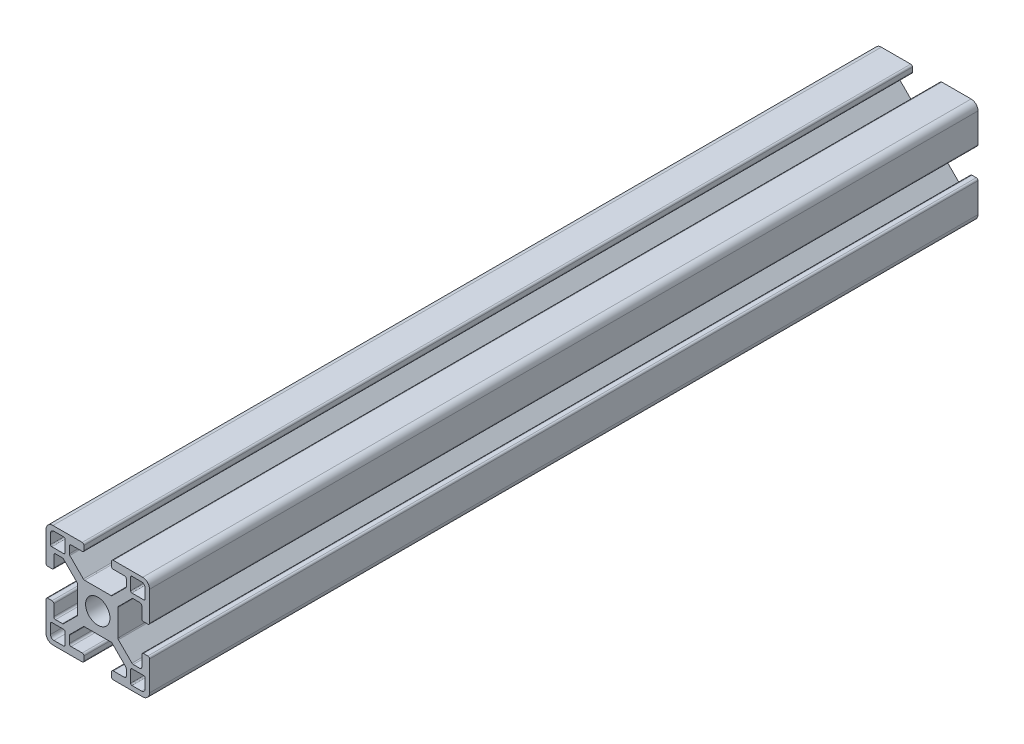
SolidWorks part; units mm, degrees
material "6063-T6"
ref_plane "Front Plane" through (0, 0, 0) normal (0, 0, 1) x (1, 0, 0)
ref_plane "Top Plane" through (0, 0, 0) normal (0, 1, 0) x (1, 0, 0)
ref_plane "Right Plane" through (0, 0, 0) normal (1, 0, 0) x (0, 0, -1)
sketch "Sketch1" plane through (0, 0, 0) normal (0, 0, 1) x (1, 0, 0)
  line L0 (3.9799, -2.4733) -> (3.1981, -1.4942) construction
  line L1 (1.4942, -3.1981) -> (2.4733, -3.9799) construction
  line L2 (-2.4733, -3.9799) -> (-1.4942, -3.1981) construction
  line L3 (-3.1981, -1.4942) -> (-3.9799, -2.4733) construction
  line L4 (-3.9799, 2.4733) -> (-3.1981, 1.4942) construction
  line L5 (-1.4942, 3.1981) -> (-2.4733, 3.9799) construction
  line L6 (2.4733, 3.9799) -> (1.4942, 3.1981) construction
  line L7 (3.1981, 1.4942) -> (3.9799, 2.4733) construction
  line L8 (-12.6999, -13.6999) -> (-9.881, -13.6999)
  line L9 (-13.6999, -9.881) -> (-13.6999, -12.6999)
  line L10 (-9.88, -9.5) -> (-13.3189, -9.5)
  line L11 (-9.5, -13.3189) -> (-9.5, -9.88)
  line L12 (13.6999, -12.6999) -> (13.6999, -9.881)
  line L13 (9.881, -13.6999) -> (12.6999, -13.6999)
  line L14 (9.5, -9.88) -> (9.5, -13.3189)
  line L15 (13.3189, -9.5) -> (9.88, -9.5)
  line L16 (9.88, 9.5) -> (13.3189, 9.5)
  line L17 (9.5, 13.3189) -> (9.5, 9.88)
  line L18 (12.6999, 13.6999) -> (9.881, 13.6999)
  line L19 (13.6999, 9.881) -> (13.6999, 12.6999)
  line L20 (-13.6999, 12.6999) -> (-13.6999, 9.881)
  line L21 (-9.881, 13.6999) -> (-12.6999, 13.6999)
  line L22 (-9.5, 9.88) -> (-9.5, 13.3189)
  line L23 (-13.3189, 9.5) -> (-9.88, 9.5)
  line L24 (14.4999, -4) -> (13.2425, -4)
  line L25 (12.7425, -4.5) -> (12.7425, -7.7325)
  line L26 (12.2428, -8.25) -> (10.2602, -8.25)
  line L27 (9.9066, -8.1035) -> (5.9811, -4.178)
  line L28 (5.8347, -3.8245) -> (5.8347, -1.0125)
  line L29 (5.8347, -1.0125) -> (5.3247, -0.0625) construction
  line L30 (5.3247, -0.0625) -> (5.8347, 0.8875) construction
  line L31 (5.8347, 0.8875) -> (5.8347, 3.8245)
  line L32 (5.9811, 4.178) -> (9.9066, 8.1035)
  line L33 (10.2602, 8.25) -> (12.2428, 8.25)
  line L34 (12.7425, 7.7325) -> (12.7425, 4.5)
  line L35 (13.2425, 4) -> (14.4999, 4)
  line L36 (14.9999, 4.5) -> (14.9999, 12.9999)
  line L37 (12.9999, 14.9999) -> (4.5, 14.9999)
  line L38 (4, 14.4999) -> (4, 13.2425)
  line L39 (4.5, 12.7425) -> (7.7325, 12.7425)
  line L40 (8.25, 12.2428) -> (8.25, 10.2602)
  line L41 (8.1035, 9.9066) -> (4.178, 5.9811)
  line L42 (3.8245, 5.8347) -> (0.95, 5.8347)
  line L43 (0.95, 5.8347) -> (0, 5.3247) construction
  line L44 (0, 5.3247) -> (-0.95, 5.8347) construction
  line L45 (-0.95, 5.8347) -> (-3.8245, 5.8347)
  line L46 (-4.178, 5.9811) -> (-8.1035, 9.9066)
  line L47 (-8.25, 10.2602) -> (-8.25, 12.2428)
  line L48 (-7.7325, 12.7425) -> (-4.5, 12.7425)
  line L49 (-4, 13.2425) -> (-4, 14.4999)
  line L50 (-4.5, 14.9999) -> (-12.9999, 14.9999)
  line L51 (-14.9999, 12.9999) -> (-14.9999, 4.5)
  line L52 (-14.4999, 4) -> (-13.2425, 4)
  line L53 (-12.7425, 4.5) -> (-12.7425, 7.7325)
  line L54 (-12.2428, 8.25) -> (-10.2602, 8.25)
  line L55 (-9.9066, 8.1035) -> (-5.9811, 4.178)
  line L56 (-5.8347, 3.8245) -> (-5.8347, 0.8875)
  line L57 (-5.8347, 0.8875) -> (-5.3247, -0.0625) construction
  line L58 (-5.3247, -0.0625) -> (-5.8347, -1.0125) construction
  line L59 (-5.8347, -1.0125) -> (-5.8347, -3.8245)
  line L60 (-5.9811, -4.178) -> (-9.9066, -8.1035)
  line L61 (-10.2602, -8.25) -> (-12.2428, -8.25)
  line L62 (-12.7425, -7.7325) -> (-12.7425, -4.5)
  line L63 (-13.2425, -4) -> (-14.4999, -4)
  line L64 (-14.9999, -4.5) -> (-14.9999, -12.9999)
  line L65 (-12.9999, -14.9999) -> (-4.5, -14.9999)
  line L66 (-4, -14.4999) -> (-4, -13.2425)
  line L67 (-4.5, -12.7425) -> (-7.7325, -12.7425)
  line L68 (-8.25, -12.2428) -> (-8.25, -10.2602)
  line L69 (-8.1035, -9.9066) -> (-4.178, -5.9811)
  line L70 (-3.8245, -5.8347) -> (-0.95, -5.8347)
  line L71 (-0.95, -5.8347) -> (0, -5.3247) construction
  line L72 (0, -5.3247) -> (0.95, -5.8347) construction
  line L73 (0.95, -5.8347) -> (3.8245, -5.8347)
  line L74 (4.178, -5.9811) -> (8.1035, -9.9066)
  line L75 (8.25, -10.2602) -> (8.25, -12.2428)
  line L76 (7.7325, -12.7425) -> (4.5, -12.7425)
  line L77 (4, -13.2425) -> (4, -14.4999)
  line L78 (4.5, -14.9999) -> (12.9999, -14.9999)
  line L79 (14.9999, -12.9999) -> (14.9999, -4.5)
  line L80 (-5.8347, -1.0125) -> (-5.8347, 0.8875)
  line L81 (-0.95, 5.8347) -> (0.95, 5.8347)
  line L82 (5.8347, 0.8875) -> (5.8347, -1.0125)
  line L83 (-0.95, -5.8347) -> (0.95, -5.8347)
  arc A0 (2.4733, -3.9799) -> (3.9799, -2.4733) centre (3.1422, -3.1422) ccw construction
  arc A1 (-1.4942, -3.1981) -> (1.4942, -3.1981) centre (0, 0) ccw construction
  arc A2 (-3.9799, -2.4733) -> (-2.4733, -3.9799) centre (-3.1422, -3.1422) ccw construction
  arc A3 (-3.1981, 1.4942) -> (-3.1981, -1.4942) centre (0, 0) ccw construction
  arc A4 (-2.4733, 3.9799) -> (-3.9799, 2.4733) centre (-3.1422, 3.1422) ccw construction
  arc A5 (1.4942, 3.1981) -> (-1.4942, 3.1981) centre (0, 0) ccw construction
  arc A6 (3.9799, 2.4733) -> (2.4733, 3.9799) centre (3.1422, 3.1422) ccw construction
  arc A7 (3.1981, -1.4942) -> (3.1981, 1.4942) centre (0, 0) ccw construction
  arc A8 (-13.6999, -12.6999) -> (-12.6999, -13.6999) centre (-12.6999, -12.6999) ccw
  arc A9 (-13.3189, -9.5) -> (-13.6999, -9.881) centre (-13.3189, -9.881) ccw
  arc A10 (-9.5, -9.88) -> (-9.88, -9.5) centre (-9.88, -9.88) ccw
  arc A11 (-9.881, -13.6999) -> (-9.5, -13.3189) centre (-9.881, -13.3189) ccw
  arc A12 (12.6999, -13.6999) -> (13.6999, -12.6999) centre (12.6999, -12.6999) ccw
  arc A13 (9.5, -13.3189) -> (9.881, -13.6999) centre (9.881, -13.3189) ccw
  arc A14 (9.88, -9.5) -> (9.5, -9.88) centre (9.88, -9.88) ccw
  arc A15 (13.6999, -9.881) -> (13.3189, -9.5) centre (13.3189, -9.881) ccw
  arc A16 (9.5, 9.88) -> (9.88, 9.5) centre (9.88, 9.88) ccw
  arc A17 (9.881, 13.6999) -> (9.5, 13.3189) centre (9.881, 13.3189) ccw
  arc A18 (13.6999, 12.6999) -> (12.6999, 13.6999) centre (12.6999, 12.6999) ccw
  arc A19 (13.3189, 9.5) -> (13.6999, 9.881) centre (13.3189, 9.881) ccw
  arc A20 (14.9999, -4.5) -> (14.4999, -4) centre (14.4999, -4.5) ccw
  arc A21 (13.2425, -4) -> (12.7425, -4.5) centre (13.2425, -4.5) ccw
  arc A22 (12.2428, -8.25) -> (12.7425, -7.7325) centre (12.2428, -7.75) ccw
  arc A23 (9.9066, -8.1035) -> (10.2602, -8.25) centre (10.2602, -7.75) ccw
  arc A24 (5.8347, -3.8245) -> (5.9811, -4.178) centre (6.3347, -3.8245) ccw
  arc A25 (5.9811, 4.178) -> (5.8347, 3.8245) centre (6.3347, 3.8245) ccw
  arc A26 (10.2602, 8.25) -> (9.9066, 8.1035) centre (10.2602, 7.75) ccw
  arc A27 (12.7425, 7.7325) -> (12.2428, 8.25) centre (12.2428, 7.75) ccw
  arc A28 (12.7425, 4.5) -> (13.2425, 4) centre (13.2425, 4.5) ccw
  arc A29 (14.4999, 4) -> (14.9999, 4.5) centre (14.4999, 4.5) ccw
  arc A30 (14.9999, 12.9999) -> (12.9999, 14.9999) centre (12.9999, 12.9999) ccw
  arc A31 (4.5, 14.9999) -> (4, 14.4999) centre (4.5, 14.4999) ccw
  arc A32 (4, 13.2425) -> (4.5, 12.7425) centre (4.5, 13.2425) ccw
  arc A33 (8.25, 12.2428) -> (7.7325, 12.7425) centre (7.75, 12.2428) ccw
  arc A34 (8.1035, 9.9066) -> (8.25, 10.2602) centre (7.75, 10.2602) ccw
  arc A35 (3.8245, 5.8347) -> (4.178, 5.9811) centre (3.8245, 6.3347) ccw
  arc A36 (-4.178, 5.9811) -> (-3.8245, 5.8347) centre (-3.8245, 6.3347) ccw
  arc A37 (-8.25, 10.2602) -> (-8.1035, 9.9066) centre (-7.75, 10.2602) ccw
  arc A38 (-7.7325, 12.7425) -> (-8.25, 12.2428) centre (-7.75, 12.2428) ccw
  arc A39 (-4.5, 12.7425) -> (-4, 13.2425) centre (-4.5, 13.2425) ccw
  arc A40 (-4, 14.4999) -> (-4.5, 14.9999) centre (-4.5, 14.4999) ccw
  arc A41 (-12.9999, 14.9999) -> (-14.9999, 12.9999) centre (-12.9999, 12.9999) ccw
  arc A42 (-14.9999, 4.5) -> (-14.4999, 4) centre (-14.4999, 4.5) ccw
  arc A43 (-13.2425, 4) -> (-12.7425, 4.5) centre (-13.2425, 4.5) ccw
  arc A44 (-12.2428, 8.25) -> (-12.7425, 7.7325) centre (-12.2428, 7.75) ccw
  arc A45 (-9.9066, 8.1035) -> (-10.2602, 8.25) centre (-10.2602, 7.75) ccw
  arc A46 (-5.8347, 3.8245) -> (-5.9811, 4.178) centre (-6.3347, 3.8245) ccw
  arc A47 (-5.9811, -4.178) -> (-5.8347, -3.8245) centre (-6.3347, -3.8245) ccw
  arc A48 (-10.2602, -8.25) -> (-9.9066, -8.1035) centre (-10.2602, -7.75) ccw
  arc A49 (-12.7425, -7.7325) -> (-12.2428, -8.25) centre (-12.2428, -7.75) ccw
  arc A50 (-12.7425, -4.5) -> (-13.2425, -4) centre (-13.2425, -4.5) ccw
  arc A51 (-14.4999, -4) -> (-14.9999, -4.5) centre (-14.4999, -4.5) ccw
  arc A52 (-14.9999, -12.9999) -> (-12.9999, -14.9999) centre (-12.9999, -12.9999) ccw
  arc A53 (-4.5, -14.9999) -> (-4, -14.4999) centre (-4.5, -14.4999) ccw
  arc A54 (-4, -13.2425) -> (-4.5, -12.7425) centre (-4.5, -13.2425) ccw
  arc A55 (-8.25, -12.2428) -> (-7.7325, -12.7425) centre (-7.75, -12.2428) ccw
  arc A56 (-8.1035, -9.9066) -> (-8.25, -10.2602) centre (-7.75, -10.2602) ccw
  arc A57 (-3.8245, -5.8347) -> (-4.178, -5.9811) centre (-3.8245, -6.3347) ccw
  arc A58 (4.178, -5.9811) -> (3.8245, -5.8347) centre (3.8245, -6.3347) ccw
  arc A59 (8.25, -10.2602) -> (8.1035, -9.9066) centre (7.75, -10.2602) ccw
  arc A60 (7.7325, -12.7425) -> (8.25, -12.2428) centre (7.75, -12.2428) ccw
  arc A61 (4.5, -12.7425) -> (4, -13.2425) centre (4.5, -13.2425) ccw
  arc A62 (4, -14.4999) -> (4.5, -14.9999) centre (4.5, -14.4999) ccw
  arc A63 (12.9999, -14.9999) -> (14.9999, -12.9999) centre (12.9999, -12.9999) ccw
  arc A64 (-12.6999, 13.6999) -> (-13.6999, 12.6999) centre (-12.6999, 12.6999) ccw
  arc A65 (-9.5, 13.3189) -> (-9.881, 13.6999) centre (-9.881, 13.3189) ccw
  arc A66 (-9.88, 9.5) -> (-9.5, 9.88) centre (-9.88, 9.88) ccw
  arc A67 (-13.6999, 9.881) -> (-13.3189, 9.5) centre (-13.3189, 9.881) ccw
  circle A68 centre (0, 0) radius 3.53
extrude "Boss-Extrude1" add sketch "Sketch1" along normal mid plane 240
